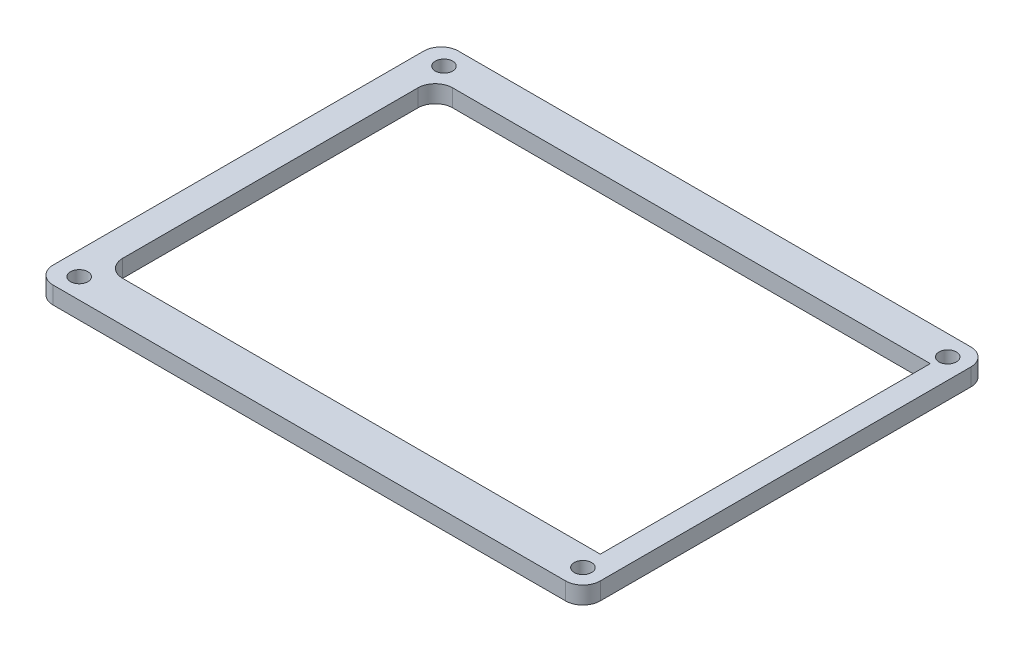
SolidWorks part; units mm, degrees
material "Acrylic (Medium-high impact)"
ref_plane "Front Plane" through (0, 0, 0) normal (0, 0, 1) x (1, 0, 0)
ref_plane "Top Plane" through (0, 0, 0) normal (0, 1, 0) x (1, 0, 0)
ref_plane "Right Plane" through (0, 0, 0) normal (1, 0, 0) x (0, 0, -1)
sketch "Sketch1" plane through (0, 0, 0) normal (0, 1, 0) x (1, 0, 0)
  line L1 (-47.25, 35) -> (47.25, 35)
  line L2 (-47.25, 35) -> (-47.25, -35)
  line L3 (-47.25, -35) -> (47.25, -35)
  line L4 (47.25, 35) -> (47.25, -35)
  line L5 (-47.25, 35) -> (47.25, -35) construction
  line L6 (-47.25, -35) -> (47.25, 35) construction
  point P0 (0, 0)
  dimension "D1" = 70
  dimension "D2" = 94.5
extrude "Boss-Extrude1" add sketch "Sketch1" along normal blind 3
sketch "Sketch3" plane through (0, 3, 0) normal (0, 1, 0) x (1, 0, 0)
  line L0 (47.25, -35) -> (47.25, 35) construction
  line L2 (47.25, 35) -> (-47.25, 35) construction
  circle A0 centre (43.75, 31.5) radius 1.5
  circle A1 centre (-43.25, 31.5) radius 1.5
  circle A2 centre (-43.25, -31.5) radius 1.5
  circle A3 centre (43.75, -31.5) radius 1.5
  dimension "D1" = 3
  dimension "D2" = 3.5
  dimension "D3" = 3.5
  dimension "D4" = 2
  dimension "D5" = 87
  dimension "D6" = 63
  dimension "D7" = 2
extrude "Cut-Extrude2" cut sketch "Sketch3" against normal through all
fillet "Fillet2" radius 3 4 edges at (-47.25, 1.5, 35) (-47.25, 1.5, -35) (47.25, 1.5, -35) (47.25, 1.5, 35)
sketch "Sketch5" plane through (0, 3, 0) normal (0, 1, 0) x (1, 0, 0)
  line L0 (-42.25, 29) -> (43.25, 29)
  line L3 (-42.25, -28) -> (-42.25, 29)
  line L15 (-35, -28) -> (43.25, -28)
  line L17 (44.25, 35) -> (-44.25, 35) construction
  line L18 (-47.25, 32) -> (-47.25, -32) construction
  line L21 (-39.25, -31) -> (-39.25, -35)
  line L22 (-44.25, -35) -> (44.25, -35) construction
  line L23 (-39.25, -35) -> (20.75, -35)
  line L24 (20.75, -35) -> (20.75, -31)
  line L25 (20.75, -31) -> (-39.25, -31)
  line L27 (43.25, 29) -> (43.25, -28)
  line L28 (-35, -28) -> (-42.25, -28)
  line L29 (47.25, -32) -> (47.25, 32) construction
  line L30 (-42.25, 10) -> (-47.25, 10)
  line L31 (-47.25, 10) -> (-47.25, -10)
  line L32 (-47.25, -10) -> (-42.25, -10)
  dimension "D1" = 6
  dimension "D2" = 5
  dimension "D3" = 4
  dimension "D4" = 57
  dimension "D5" = 25
  dimension "D6" = 4
  dimension "D7" = 20
  dimension "D14" = 60
  dimension "D15" = 8
extrude "Cut-Extrude3" cut sketch "Sketch5" against normal through all
fillet "Fillet3" radius 3 2 edges at (-42.25, 1.5, -29) (-42.25, 1.5, 28)
